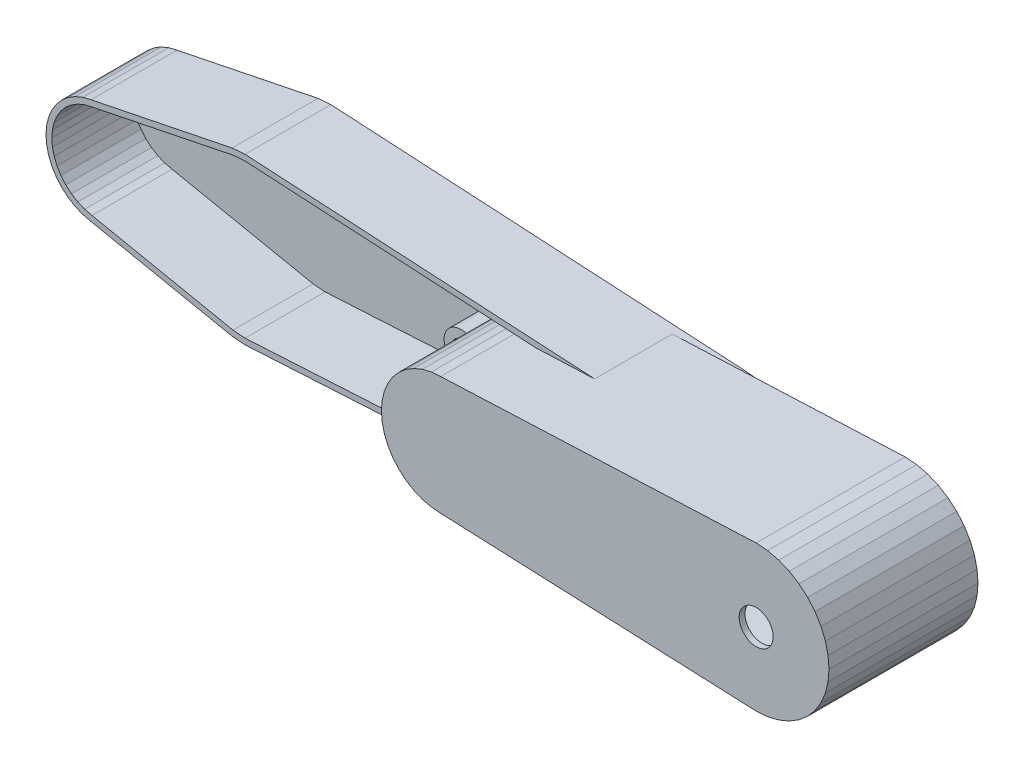
SolidWorks part; units mm, degrees
ref_plane "Front Plane" through (0, 0, 0) normal (0, 0, 1) x (1, 0, 0)
ref_plane "Top Plane" through (0, 0, 0) normal (0, 1, 0) x (1, 0, 0)
ref_plane "Right Plane" through (0, 0, 0) normal (1, 0, 0) x (0, 0, -1)
sketch "Sketch1" plane through (0, 0, 0) normal (0, 0, 1) x (1, 0, 0)
  line L0 (-41, 0) -> (-40.8646, -1.7208)
  line L1 (-40.8646, -1.7208) -> (-40.4616, -3.3992)
  line L2 (-40.4616, -3.3992) -> (-39.8011, -4.9939)
  line L3 (-39.8011, -4.9939) -> (-38.8992, -6.4656)
  line L4 (-38.8992, -6.4656) -> (-37.7782, -7.7782)
  line L5 (-37.7782, -7.7782) -> (-36.4656, -8.8992)
  line L6 (-36.4656, -8.8992) -> (-34.9939, -9.8011)
  line L7 (-34.9939, -9.8011) -> (-33.3992, -10.4616)
  line L8 (-33.3992, -10.4616) -> (-31.7208, -10.8646)
  line L9 (-31.7208, -10.8646) -> (-2.6594, -16.7907)
  line L10 (-2.6594, -16.7907) -> (0, -17)
  line L11 (0, -17) -> (85, -12.2)
  line L12 (85, -12.2) -> (86.9085, -12.0498)
  line L13 (86.9085, -12.0498) -> (88.77, -11.6029)
  line L14 (88.77, -11.6029) -> (90.5387, -10.8703)
  line L15 (90.5387, -10.8703) -> (92.171, -9.87)
  line L16 (92.171, -9.87) -> (93.6267, -8.6267)
  line L17 (93.6267, -8.6267) -> (94.87, -7.171)
  line L18 (94.87, -7.171) -> (95.8703, -5.5387)
  line L19 (95.8703, -5.5387) -> (96.6029, -3.77)
  line L20 (96.6029, -3.77) -> (97.0498, -1.9085)
  line L21 (97.0498, -1.9085) -> (97.2, 0)
  line L22 (97.2, 0) -> (97.0498, 1.9085)
  line L23 (97.0498, 1.9085) -> (96.6029, 3.77)
  line L24 (96.6029, 3.77) -> (95.8703, 5.5387)
  line L25 (95.8703, 5.5387) -> (94.87, 7.171)
  line L26 (94.87, 7.171) -> (93.6267, 8.6267)
  line L27 (93.6267, 8.6267) -> (92.171, 9.87)
  line L28 (92.171, 9.87) -> (90.5387, 10.8703)
  line L29 (90.5387, 10.8703) -> (88.77, 11.6029)
  line L30 (88.77, 11.6029) -> (86.9085, 12.0498)
  line L31 (86.9085, 12.0498) -> (85, 12.2)
  line L32 (85, 12.2) -> (0, 17)
  line L33 (0, 17) -> (-2.6594, 16.7907)
  line L34 (-2.6594, 16.7907) -> (-31.7208, 10.8646)
  line L35 (-31.7208, 10.8646) -> (-33.3992, 10.4616)
  line L36 (-33.3992, 10.4616) -> (-34.9939, 9.8011)
  line L37 (-34.9939, 9.8011) -> (-36.4656, 8.8992)
  line L38 (-36.4656, 8.8992) -> (-37.7782, 7.7782)
  line L39 (-37.7782, 7.7782) -> (-38.8992, 6.4656)
  line L40 (-38.8992, 6.4656) -> (-39.8011, 4.9939)
  line L41 (-39.8011, 4.9939) -> (-40.4616, 3.3992)
  line L42 (-40.4616, 3.3992) -> (-40.8646, 1.7208)
  line L43 (-40.8646, 1.7208) -> (-41, 0)
extrude "Boss-Extrude1" add sketch "Sketch1" along normal blind 17.7 from offset 22.2
sketch "Sketch2" plane through (0, 0, 0) normal (0, 0, 1) x (1, 0, 0)
  line L0 (-39.8, 0) -> (-39.6793, -1.5331)
  line L1 (-39.6793, -1.5331) -> (-39.3204, -3.0284)
  line L2 (-39.3204, -3.0284) -> (-38.7319, -4.4491)
  line L3 (-38.7319, -4.4491) -> (-37.9284, -5.7603)
  line L4 (-37.9284, -5.7603) -> (-36.9296, -6.9296)
  line L5 (-36.9296, -6.9296) -> (-35.7603, -7.9284)
  line L6 (-35.7603, -7.9284) -> (-34.4491, -8.7319)
  line L7 (-34.4491, -8.7319) -> (-33.0284, -9.3204)
  line L8 (-33.0284, -9.3204) -> (-31.5331, -9.6793)
  line L9 (-31.5331, -9.6793) -> (-2.4717, -15.6055)
  line L10 (-2.4717, -15.6055) -> (0, -15.8)
  line L11 (0, -15.8) -> (85, -11)
  line L12 (85, -11) -> (86.7208, -10.8646)
  line L13 (86.7208, -10.8646) -> (88.3992, -10.4616)
  line L14 (88.3992, -10.4616) -> (89.9939, -9.8011)
  line L15 (89.9939, -9.8011) -> (91.4656, -8.8992)
  line L16 (91.4656, -8.8992) -> (92.7782, -7.7782)
  line L17 (92.7782, -7.7782) -> (93.8992, -6.4656)
  line L18 (93.8992, -6.4656) -> (94.8011, -4.9939)
  line L19 (94.8011, -4.9939) -> (95.4616, -3.3992)
  line L20 (95.4616, -3.3992) -> (95.8646, -1.7208)
  line L21 (95.8646, -1.7208) -> (96, 0)
  line L22 (96, 0) -> (95.8646, 1.7208)
  line L23 (95.8646, 1.7208) -> (95.4616, 3.3992)
  line L24 (95.4616, 3.3992) -> (94.8011, 4.9939)
  line L25 (94.8011, 4.9939) -> (93.8992, 6.4656)
  line L26 (93.8992, 6.4656) -> (92.7782, 7.7782)
  line L27 (92.7782, 7.7782) -> (91.4656, 8.8992)
  line L28 (91.4656, 8.8992) -> (89.9939, 9.8011)
  line L29 (89.9939, 9.8011) -> (88.3992, 10.4616)
  line L30 (88.3992, 10.4616) -> (86.7208, 10.8646)
  line L31 (86.7208, 10.8646) -> (85, 11)
  line L32 (85, 11) -> (0, 15.8)
  line L33 (0, 15.8) -> (-2.4717, 15.6055)
  line L34 (-2.4717, 15.6055) -> (-31.5331, 9.6793)
  line L35 (-31.5331, 9.6793) -> (-33.0284, 9.3204)
  line L36 (-33.0284, 9.3204) -> (-34.4491, 8.7319)
  line L37 (-34.4491, 8.7319) -> (-35.7603, 7.9284)
  line L38 (-35.7603, 7.9284) -> (-36.9296, 6.9296)
  line L39 (-36.9296, 6.9296) -> (-37.9284, 5.7603)
  line L40 (-37.9284, 5.7603) -> (-38.7319, 4.4491)
  line L41 (-38.7319, 4.4491) -> (-39.3204, 3.0284)
  line L42 (-39.3204, 3.0284) -> (-39.6793, 1.5331)
  line L43 (-39.6793, 1.5331) -> (-39.8, 0)
extrude "Cut-Extrude1" cut sketch "Sketch2" along normal blind 16.6 from offset 21
sketch "Sketch3" plane through (0, 0, 0) normal (0, 0, 1) x (1, 0, 0)
  line L0 (42.8, 0) -> (42.9502, -1.9085)
  line L1 (42.9502, -1.9085) -> (43.3971, -3.77)
  line L2 (43.3971, -3.77) -> (44.1297, -5.5387)
  line L3 (44.1297, -5.5387) -> (45.13, -7.171)
  line L4 (45.13, -7.171) -> (46.3733, -8.6267)
  line L5 (46.3733, -8.6267) -> (47.829, -9.87)
  line L6 (47.829, -9.87) -> (49.4613, -10.8703)
  line L7 (49.4613, -10.8703) -> (51.23, -11.6029)
  line L8 (51.23, -11.6029) -> (53.0915, -12.0498)
  line L9 (53.0915, -12.0498) -> (55, -12.2)
  line L10 (55, -12.2) -> (120, -15)
  line L11 (120, -15) -> (122.3465, -14.8153)
  line L12 (122.3465, -14.8153) -> (124.6353, -14.2658)
  line L13 (124.6353, -14.2658) -> (126.8099, -13.3651)
  line L14 (126.8099, -13.3651) -> (128.8168, -12.1353)
  line L15 (128.8168, -12.1353) -> (130.6066, -10.6066)
  line L16 (130.6066, -10.6066) -> (132.1353, -8.8168)
  line L17 (132.1353, -8.8168) -> (133.3651, -6.8099)
  line L18 (133.3651, -6.8099) -> (134.2658, -4.6353)
  line L19 (134.2658, -4.6353) -> (134.8153, -2.3465)
  line L20 (134.8153, -2.3465) -> (135, 0)
  line L21 (135, 0) -> (134.8153, 2.3465)
  line L22 (134.8153, 2.3465) -> (134.2658, 4.6353)
  line L23 (134.2658, 4.6353) -> (133.3651, 6.8099)
  line L24 (133.3651, 6.8099) -> (132.1353, 8.8168)
  line L25 (132.1353, 8.8168) -> (130.6066, 10.6066)
  line L26 (130.6066, 10.6066) -> (128.8168, 12.1353)
  line L27 (128.8168, 12.1353) -> (126.8099, 13.3651)
  line L28 (126.8099, 13.3651) -> (124.6353, 14.2658)
  line L29 (124.6353, 14.2658) -> (122.3465, 14.8153)
  line L30 (122.3465, 14.8153) -> (120, 15)
  line L31 (120, 15) -> (55, 12.2)
  line L32 (55, 12.2) -> (53.0915, 12.0498)
  line L33 (53.0915, 12.0498) -> (51.23, 11.6029)
  line L34 (51.23, 11.6029) -> (49.4613, 10.8703)
  line L35 (49.4613, 10.8703) -> (47.829, 9.87)
  line L36 (47.829, 9.87) -> (46.3733, 8.6267)
  line L37 (46.3733, 8.6267) -> (45.13, 7.171)
  line L38 (45.13, 7.171) -> (44.1297, 5.5387)
  line L39 (44.1297, 5.5387) -> (43.3971, 3.77)
  line L40 (43.3971, 3.77) -> (42.9502, 1.9085)
  line L41 (42.9502, 1.9085) -> (42.8, 0)
extrude "Boss-Extrude2" add sketch "Sketch3" along normal blind 30.7 from offset 20.5
sketch "Sketch4" plane through (0, 0, 0) normal (0, 0, 1) x (1, 0, 0)
  line L0 (44, 0) -> (44.1354, -1.7208)
  line L1 (44.1354, -1.7208) -> (44.5384, -3.3992)
  line L2 (44.5384, -3.3992) -> (45.1989, -4.9939)
  line L3 (45.1989, -4.9939) -> (46.1008, -6.4656)
  line L4 (46.1008, -6.4656) -> (47.2218, -7.7782)
  line L5 (47.2218, -7.7782) -> (48.5344, -8.8992)
  line L6 (48.5344, -8.8992) -> (50.0061, -9.8011)
  line L7 (50.0061, -9.8011) -> (51.6008, -10.4616)
  line L8 (51.6008, -10.4616) -> (53.2792, -10.8646)
  line L9 (53.2792, -10.8646) -> (55, -11)
  line L10 (55, -11) -> (120, -13.8)
  line L11 (120, -13.8) -> (122.1588, -13.6301)
  line L12 (122.1588, -13.6301) -> (124.2644, -13.1246)
  line L13 (124.2644, -13.1246) -> (126.2651, -12.2959)
  line L14 (126.2651, -12.2959) -> (128.1114, -11.1644)
  line L15 (128.1114, -11.1644) -> (129.7581, -9.7581)
  line L16 (129.7581, -9.7581) -> (131.1644, -8.1114)
  line L17 (131.1644, -8.1114) -> (132.2959, -6.2651)
  line L18 (132.2959, -6.2651) -> (133.1246, -4.2644)
  line L19 (133.1246, -4.2644) -> (133.6301, -2.1588)
  line L20 (133.6301, -2.1588) -> (133.8, 0)
  line L21 (133.8, 0) -> (133.6301, 2.1588)
  line L22 (133.6301, 2.1588) -> (133.1246, 4.2644)
  line L23 (133.1246, 4.2644) -> (132.2959, 6.2651)
  line L24 (132.2959, 6.2651) -> (131.1644, 8.1114)
  line L25 (131.1644, 8.1114) -> (129.7581, 9.7581)
  line L26 (129.7581, 9.7581) -> (128.1114, 11.1644)
  line L27 (128.1114, 11.1644) -> (126.2651, 12.2959)
  line L28 (126.2651, 12.2959) -> (124.2644, 13.1246)
  line L29 (124.2644, 13.1246) -> (122.1588, 13.6301)
  line L30 (122.1588, 13.6301) -> (120, 13.8)
  line L31 (120, 13.8) -> (55, 11)
  line L32 (55, 11) -> (53.2792, 10.8646)
  line L33 (53.2792, 10.8646) -> (51.6008, 10.4616)
  line L34 (51.6008, 10.4616) -> (50.0061, 9.8011)
  line L35 (50.0061, 9.8011) -> (48.5344, 8.8992)
  line L36 (48.5344, 8.8992) -> (47.2218, 7.7782)
  line L37 (47.2218, 7.7782) -> (46.1008, 6.4656)
  line L38 (46.1008, 6.4656) -> (45.1989, 4.9939)
  line L39 (45.1989, 4.9939) -> (44.5384, 3.3992)
  line L40 (44.5384, 3.3992) -> (44.1354, 1.7208)
  line L41 (44.1354, 1.7208) -> (44, 0)
extrude "Cut-Extrude2" cut sketch "Sketch4" along normal blind 29.6 from offset 20.6
sketch "Sketch5" plane through (0, 0, 0) normal (0, 0, 1) x (1, 0, 0)
  circle A0 centre (120, 0) radius 3.5
extrude "Cut-Extrude3" cut sketch "Sketch5" along normal blind 1.4 from offset 8.9
sketch "Sketch6" plane through (0, 0, 0) normal (0, 0, 1) x (1, 0, 0)
  line L0 (40, -8.6) -> (57, -8.6)
  line L1 (57, -8.6) -> (57, 8.6)
  line L2 (57, 8.6) -> (40, 8.6)
  line L3 (40, 8.6) -> (40, -8.6)
extrude "Cut-Extrude4" cut sketch "Sketch6" along normal blind 17 from offset 20.6
sketch "Sketch7" plane through (0, 0, 0) normal (0, 0, 1) x (1, 0, 0)
  circle A0 centre (40, 0) radius 3.5
  circle A1 centre (75, 0) radius 3.5
extrude "Boss-Extrude3" add sketch "Sketch7" along normal blind 12 from offset 21
sketch "Sketch8" plane through (0, 0, 0) normal (0, 0, 1) x (1, 0, 0)
  circle A0 centre (40, 0) radius 1.725
  circle A1 centre (75, 0) radius 1.725
extrude "Cut-Extrude5" cut sketch "Sketch8" along normal blind 13.3 from offset 22.3
